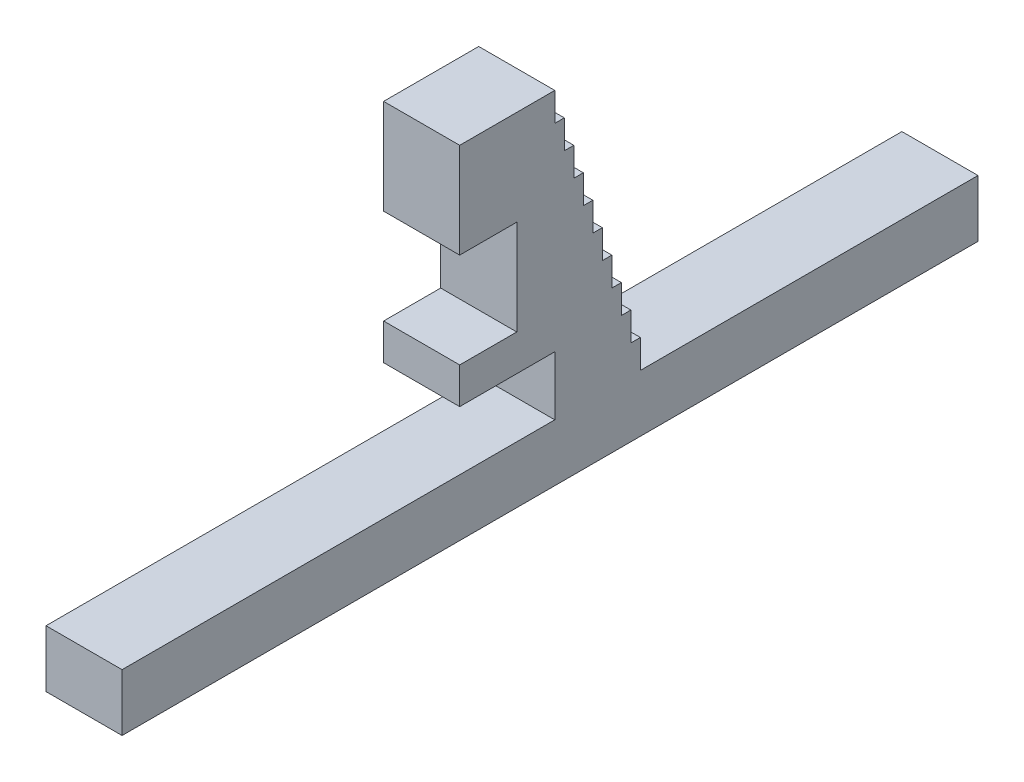
SolidWorks part; units mm, degrees
ref_plane "Front Plane" through (0, 0, 0) normal (0, 0, 1) x (1, 0, 0)
ref_plane "Top Plane" through (0, 0, 0) normal (0, 1, 0) x (1, 0, 0)
ref_plane "Right Plane" through (0, 0, 0) normal (1, 0, 0) x (0, 0, -1)
sketch "Sketch1" plane through (0, 0, 0) normal (1, 0, 0) x (0, 0, -1)
  line L0 (4, 0) -> (21.75, 0)
  line L1 (21.75, 0) -> (21.75, -3)
  line L2 (21.75, -3) -> (-23.25, -3)
  line L3 (-23.25, -3) -> (-23.25, 0)
  line L4 (-23.25, 0) -> (-5.5, 0)
  line L29 (-5.5, 15) -> (-0.5, 15)
  line L30 (-0.5, 15) -> (-0.5, 13.5)
  line L31 (-0.5, 13.5) -> (0, 13.5)
  line L32 (0, 13.5) -> (0, 12)
  line L33 (0, 12) -> (0.5, 12)
  line L34 (0.5, 12) -> (0.5, 10.5)
  line L35 (0.5, 10.5) -> (1, 10.5)
  line L36 (1, 10.5) -> (1, 9)
  line L37 (1, 9) -> (1.5, 9)
  line L38 (1.5, 9) -> (1.5, 7.5)
  line L39 (1.5, 7.5) -> (2, 7.5)
  line L40 (2, 7.5) -> (2, 6)
  line L41 (2, 6) -> (2.5, 6)
  line L42 (2.5, 6) -> (2.5, 4.5)
  line L43 (2.5, 4.5) -> (3, 4.5)
  line L44 (3, 4.5) -> (3, 3)
  line L45 (3, 3) -> (3.5, 3)
  line L46 (3.5, 3) -> (3.5, 1.5)
  line L47 (3.5, 1.5) -> (4, 1.5)
  line L48 (4, 1.5) -> (4, 0)
  line L51 (-5.5, 0) -> (-0.5, 0)
  line L54 (-0.5, 0) -> (-0.5, 3.1)
  line L56 (-2.5, 10) -> (-5.5, 10)
  line L57 (-0.5, 3.1) -> (-5.5, 3.1)
  line L58 (-5.5, 15) -> (-5.5, 10)
  line L59 (-2.5, 10) -> (-2.5, 5)
  line L60 (-2.5, 5) -> (-5.5, 5)
  line L61 (-5.5, 5) -> (-5.5, 3.1)
  dimension "D1" = 5
  dimension "D2" = 45
  dimension "D3" = 1.5
  dimension "D4" = 3
  dimension "D5" = 5
  dimension "D6" = 0.5
  dimension "D7" = 3
  dimension "D8" = 3.1
  dimension "D9" = 5
  dimension "D10" = 5
extrude "Boss-Extrude1" add sketch "Sketch1" along normal blind 4
